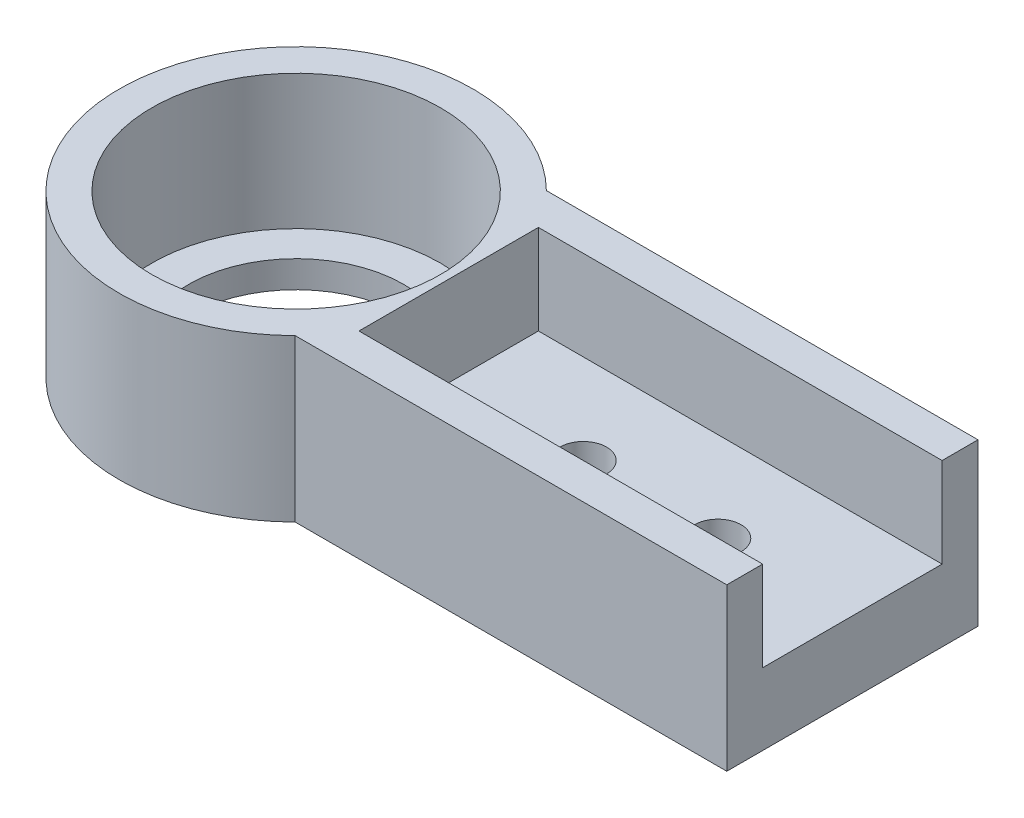
SolidWorks part; units mm, degrees
ref_plane "前视基准面" through (0, 0, 0) normal (0, 0, 1) x (1, 0, 0)
ref_plane "上视基准面" through (0, 0, 0) normal (0, 1, 0) x (1, 0, 0)
ref_plane "右视基准面" through (0, 0, 0) normal (1, 0, 0) x (0, 0, -1)
other "Configuration Table"
sketch "草图1" plane through (0, 0, 0) normal (0, 1, 0) x (1, 0, 0)
  line L4 (50, 10) -> (50, -10)
  line L5 (50, 14) -> (-3.1076, 14)
  line L6 (50, -14) -> (-3.1076, -14)
  line L9 (50, 14) -> (50, 10)
  line L11 (50, -14) -> (50, -10)
  circle A0 centre (-17, 0) radius 16
  arc A1 (-3.1076, 14) -> (-3.1076, -14) centre (-17, 0) ccw
extrude "凸台-拉伸2" add sketch "草图1" along normal blind 11 contours L5 A1 L6 L11 L4 L9 A0
sketch "草图3" plane through (0, 11, 0) normal (0, 1, 0) x (1, 0, 0)
  line L0 (0, 0) -> (0, 10)
  line L1 (0, 0) -> (0, -10)
  line L2 (0, -10) -> (45, -10)
  line L3 (0, 10) -> (45, 10)
  line L4 (45, -10) -> (45, 10)
extrude "切除-拉伸1" cut sketch "草图3" against normal blind 5
sketch "草图4" plane through (0, 11, 0) normal (0, 1, 0) x (1, 0, 0)
  line L1 (50, -14) -> (45, -14)
  line L2 (50, -14) -> (50, 10)
  line L3 (50, 10) -> (45, 10)
  line L4 (45, -14) -> (45, 10)
  line L5 (45, 10) -> (50, 10)
  line L6 (45, 10) -> (45, 14)
  line L7 (45, 14) -> (50, 14)
  line L8 (50, 10) -> (50, 14)
  line M3 (45, 10) -> (45, -10)
  line M6 (50, 14) -> (-3.1076, 14)
  line M8 (-3.1076, -14) -> (50, -14)
  line M9 (50, -14) -> (50, 14)
extrude "切除-拉伸2" cut sketch "草图4" against normal blind 11 contours L6 L3 M9 M6 | L4 L3 M8 M9 M3
sketch "草图5" plane through (0, 6, 0) normal (0, 1, 0) x (1, 0, 0)
  line L0 (0, 0) -> (15, 0)
  line L1 (45, 0) -> (30, 0)
  line L2 (45, -10) -> (45, 10) construction
  circle A0 centre (15, 0) radius 2.6
  circle A1 centre (30, 0) radius 2.6
extrude "切除-拉伸3" cut sketch "草图5" against normal blind 11
sketch "草图6" plane through (0, 0, 0) normal (0, -1, 0) x (1, 0, 0)
  circle A0 centre (15, 0) radius 5
  circle A1 centre (30, 0) radius 5
extrude "切除-拉伸4" cut sketch "草图6" against normal blind 3
sketch "草图8" plane through (0, 0, 0) normal (0, -1, 0) x (-1, 0, 0)
  circle A0 centre (17, 0) radius 16
  circle A1 centre (17, 0) radius 12
extrude "凸台-拉伸5" add sketch "草图8" against normal blind 1 contours A1 | A0
sketch "草图9" plane through (0, 0, 0) normal (0, -1, 0) x (1, 0, 0)
  line L0 (45, -14) -> (-3.1076, -14) construction
  line L1 (-3.1076, 14) -> (45, 14)
  line L2 (45, 14) -> (45, -14)
  line L3 (45, -14) -> (-3.1076, -14)
  arc A0 (-3.1076, 14) -> (-3.1076, -14) centre (-17, 0) ccw
  circle A1 centre (-17, 0) radius 12
  circle A2 centre (15, 0) radius 5
  circle A3 centre (30, 0) radius 5
extrude "凸台-拉伸6" add sketch "草图9" along normal blind 2 contours L3 A0 L1 L2 | A1 | A2 | A3
sketch "草图10" plane through (0, 11, 0) normal (0, 1, 0) x (1, 0, 0)
  circle A0 centre (-17, 0) radius 16.1
extrude "切除-拉伸5" cut sketch "草图10" against normal blind 10
sketch "草图12" plane through (0, 11, 0) normal (0, 1, 0) x (1, 0, 0)
  line L1 (-3.1076, 14) -> (45, 14)
  line L2 (-3.1076, 14) -> (-3.1076, 10)
  line L3 (-3.1076, 10) -> (45, 10)
  line L4 (45, 14) -> (45, 10)
  line L5 (-3.1076, -14) -> (45, -14)
  line L6 (-3.1076, -14) -> (-3.1076, -10)
  line L7 (-3.1076, -10) -> (45, -10)
  line L8 (45, -14) -> (45, -10)
extrude "凸台-拉伸7" add sketch "草图12" along normal blind 5
sketch "草图13" plane through (0, 11, 0) normal (0, 1, 0) x (1, 0, 0)
  line L0 (45, -10) -> (-3.1076, -10) construction
  line L1 (-3.1076, 14) -> (0, 10)
  line L2 (0, 10) -> (0, -10)
  arc A0 (-3.1076, 14) -> (0, -10) centre (-17, 0) ccw
  circle A1 centre (-17, 0) radius 16.1
extrude "凸台-拉伸8" add sketch "草图13" along normal blind 5
